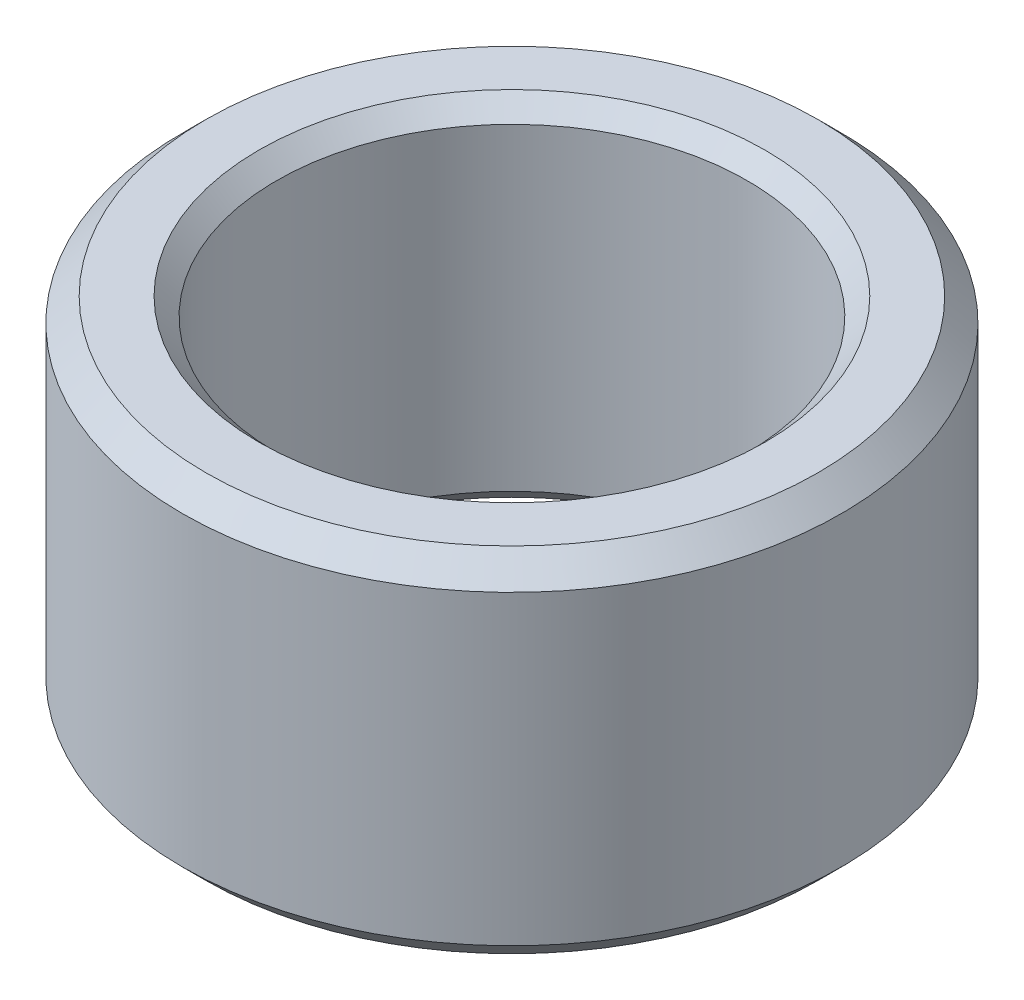
SolidWorks part; units mm, degrees
material "Пруток ДКРВМ 12 НД ЛС59-1 ГОСТ 2060-2006"
ref_plane "Спереди" through (0, 0, 0) normal (0, 0, 1) x (1, 0, 0)
ref_plane "Сверху" through (0, 0, 0) normal (0, 1, 0) x (1, 0, 0)
ref_plane "Справа" through (0, 0, 0) normal (1, 0, 0) x (0, 0, -1)
sketch "Эскиз1" plane through (0, 0, 0) normal (0, 1, 0) x (1, 0, 0)
  circle A0 centre (0, 0) radius 4
  circle A1 centre (0, 0) radius 5.6
  dimension "D1" = 8
  dimension "D2" = 11.2
extrude "Бобышка-Вытянуть1" add sketch "Эскиз1" along normal blind 6
chamfer "Фаска1" distance 0.3 angle 45 2 edges at (0, 0, 4) (0, 6, 4)
chamfer "Фаска2" distance 0.4 angle 45 2 edges at (0, 6, 5.6) (0, 0, 5.6)
